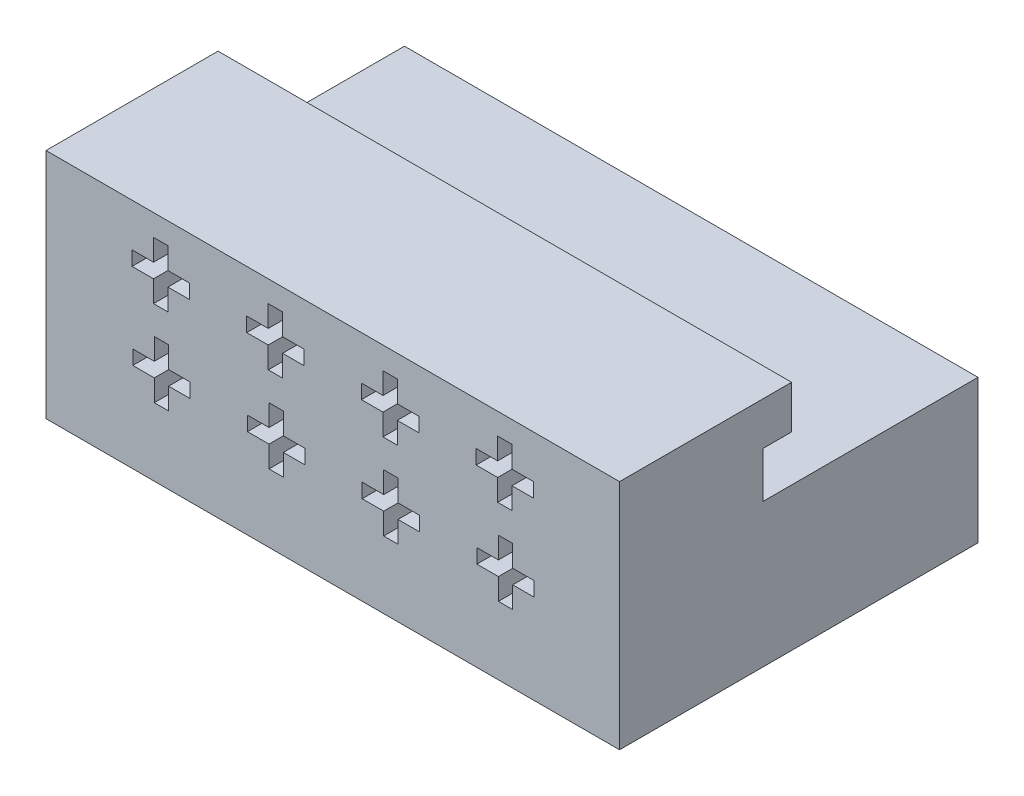
SolidWorks part; units mm, degrees
ref_plane "Front Plane" through (0, 0, 0) normal (0, 0, 1) x (1, 0, 0)
ref_plane "Top Plane" through (0, 0, 0) normal (0, 1, 0) x (1, 0, 0)
ref_plane "Right Plane" through (0, 0, 0) normal (1, 0, 0) x (0, 0, -1)
sketch "Sketch1" plane through (0, 0, 0) normal (1, 0, 0) x (0, 0, -1)
  line L0 (-9.6386, 6.2) -> (2.3614, 6.2)
  line L1 (2.3614, 6.2) -> (2.3614, 3.2)
  line L2 (2.3614, 3.2) -> (0.3614, 3.2)
  line L3 (0.3614, 3.2) -> (0.3614, 0)
  line L4 (0.3614, 0) -> (15.3614, 0)
  line L5 (15.3614, 0) -> (15.3614, -10)
  line L6 (15.3614, -10) -> (-9.6386, -10)
  line L7 (-9.6386, -10) -> (-9.6386, 6.2)
  dimension "D1" = 3.2
  dimension "D2" = 2
  dimension "D3" = 3
  dimension "D4" = 10
  dimension "D5" = 15
  dimension "D6" = 10
extrude "Boss-Extrude1" add sketch "Sketch1" along normal blind 40
sketch "Sketch2" plane through (0, 0, 9.6386) normal (0, 0, 1) x (1, 0, 0)
  line L0 (6, 3.2) -> (7.5, 3.2)
  line L1 (7.5, 3.2) -> (7.5, 4.7)
  line L2 (7.5, 4.7) -> (8.5, 4.7)
  line L3 (8.5, 4.7) -> (8.5, 3.2)
  line L4 (8.5, 3.2) -> (10, 3.2)
  line L5 (10, 3.2) -> (10, 2.2)
  line L6 (10, 2.2) -> (8.5, 2.2)
  line L7 (8.5, 2.2) -> (8.5, 0.7)
  line L8 (8.5, 0.7) -> (7.5, 0.7)
  line L9 (7.5, 0.7) -> (7.5, 2.2)
  line L10 (7.5, 2.2) -> (6, 2.2)
  line L11 (6, 2.2) -> (6, 3.2)
  line L12 (14, 3.2) -> (15.5, 3.2)
  line L13 (15.5, 3.2) -> (15.5, 4.7)
  line L14 (15.5, 4.7) -> (16.5, 4.7)
  line L15 (16.5, 4.7) -> (16.5, 3.2)
  line L16 (16.5, 3.2) -> (18, 3.2)
  line L17 (18, 3.2) -> (18, 2.2)
  line L18 (18, 2.2) -> (16.5, 2.2)
  line L19 (16.5, 2.2) -> (16.5, 0.7)
  line L20 (16.5, 0.7) -> (15.5, 0.7)
  line L21 (15.5, 0.7) -> (15.5, 2.2)
  line L22 (15.5, 2.2) -> (14, 2.2)
  line L23 (14, 2.2) -> (14, 3.2)
  line L24 (30, 3.2) -> (31.5, 3.2)
  line L25 (31.5, 3.2) -> (31.5, 4.7)
  line L26 (31.5, 4.7) -> (32.5, 4.7)
  line L27 (32.5, 4.7) -> (32.5, 3.2)
  line L28 (32.5, 3.2) -> (34, 3.2)
  line L29 (34, 3.2) -> (34, 2.2)
  line L30 (34, 2.2) -> (32.5, 2.2)
  line L31 (32.5, 2.2) -> (32.5, 0.7)
  line L32 (32.5, 0.7) -> (31.5, 0.7)
  line L33 (31.5, 0.7) -> (31.5, 2.2)
  line L34 (31.5, 2.2) -> (30, 2.2)
  line L35 (30, 2.2) -> (30, 3.2)
  line L60 (40, 6.2) -> (0, 6.2) construction
  line L61 (0, 6.2) -> (0, -10) construction
  line L62 (22, 3.1496) -> (23.5, 3.1496)
  line L63 (23.5, 3.1496) -> (23.5, 4.6496)
  line L64 (23.5, 4.6496) -> (24.5, 4.6496)
  line L65 (24.5, 4.6496) -> (24.5, 3.1496)
  line L66 (24.5, 3.1496) -> (26, 3.1496)
  line L67 (26, 3.1496) -> (26, 2.1496)
  line L68 (26, 2.1496) -> (24.5, 2.1496)
  line L69 (24.5, 2.1496) -> (24.5, 0.6496)
  line L70 (24.5, 0.6496) -> (23.5, 0.6496)
  line L71 (23.5, 0.6496) -> (23.5, 2.1496)
  line L72 (23.5, 2.1496) -> (22, 2.1496)
  line L73 (22, 2.1496) -> (22, 3.1496)
  line L74 (40, 6.2) -> (40, -10) construction
  line L75 (6.0514, -2.7582) -> (7.5514, -2.7582)
  line L76 (7.5514, -2.7582) -> (7.5514, -1.2582)
  line L77 (7.5514, -1.2582) -> (8.5514, -1.2582)
  line L78 (8.5514, -1.2582) -> (8.5514, -2.7582)
  line L79 (8.5514, -2.7582) -> (10.0514, -2.7582)
  line L80 (10.0514, -2.7582) -> (10.0514, -3.7582)
  line L81 (10.0514, -3.7582) -> (8.5514, -3.7582)
  line L82 (8.5514, -3.7582) -> (8.5514, -5.2582)
  line L83 (8.5514, -5.2582) -> (7.5514, -5.2582)
  line L84 (7.5514, -5.2582) -> (7.5514, -3.7582)
  line L85 (7.5514, -3.7582) -> (6.0514, -3.7582)
  line L86 (6.0514, -3.7582) -> (6.0514, -2.7582)
  line L87 (14.0514, -2.7582) -> (15.5514, -2.7582)
  line L88 (15.5514, -2.7582) -> (15.5514, -1.2582)
  line L89 (15.5514, -1.2582) -> (16.5514, -1.2582)
  line L90 (16.5514, -1.2582) -> (16.5514, -2.7582)
  line L91 (16.5514, -2.7582) -> (18.0514, -2.7582)
  line L92 (18.0514, -2.7582) -> (18.0514, -3.7582)
  line L93 (18.0514, -3.7582) -> (16.5514, -3.7582)
  line L94 (16.5514, -3.7582) -> (16.5514, -5.2582)
  line L95 (16.5514, -5.2582) -> (15.5514, -5.2582)
  line L96 (15.5514, -5.2582) -> (15.5514, -3.7582)
  line L97 (15.5514, -3.7582) -> (14.0514, -3.7582)
  line L98 (14.0514, -3.7582) -> (14.0514, -2.7582)
  line L99 (30.0514, -2.7582) -> (31.5514, -2.7582)
  line L100 (31.5514, -2.7582) -> (31.5514, -1.2582)
  line L101 (31.5514, -1.2582) -> (32.5514, -1.2582)
  line L102 (32.5514, -1.2582) -> (32.5514, -2.7582)
  line L103 (32.5514, -2.7582) -> (34.0514, -2.7582)
  line L104 (34.0514, -2.7582) -> (34.0514, -3.7582)
  line L105 (34.0514, -3.7582) -> (32.5514, -3.7582)
  line L106 (32.5514, -3.7582) -> (32.5514, -5.2582)
  line L107 (32.5514, -5.2582) -> (31.5514, -5.2582)
  line L108 (31.5514, -5.2582) -> (31.5514, -3.7582)
  line L109 (31.5514, -3.7582) -> (30.0514, -3.7582)
  line L110 (30.0514, -3.7582) -> (30.0514, -2.7582)
  line L111 (22.0514, -2.8086) -> (23.5514, -2.8086)
  line L112 (23.5514, -2.8086) -> (23.5514, -1.3086)
  line L113 (23.5514, -1.3086) -> (24.5514, -1.3086)
  line L114 (24.5514, -1.3086) -> (24.5514, -2.8086)
  line L115 (24.5514, -2.8086) -> (26.0514, -2.8086)
  line L116 (26.0514, -2.8086) -> (26.0514, -3.8086)
  line L117 (26.0514, -3.8086) -> (24.5514, -3.8086)
  line L118 (24.5514, -3.8086) -> (24.5514, -5.3086)
  line L119 (24.5514, -5.3086) -> (23.5514, -5.3086)
  line L120 (23.5514, -5.3086) -> (23.5514, -3.8086)
  line L121 (23.5514, -3.8086) -> (22.0514, -3.8086)
  line L122 (22.0514, -3.8086) -> (22.0514, -2.8086)
  point P48 (0, 0)
  point P49 (0, 0)
  point P52 (22, 2.6496)
  point P62 (16, 4.7)
  point P63 (6, 2.7)
  point P66 (14, 2.7)
  point P108 (22.0514, -3.3086)
  point P109 (16.0514, -1.2582)
  point P110 (6.0514, -3.2582)
  point P111 (14.0514, -3.2582)
  dimension "D1" = 1
  dimension "D2" = 1
  dimension "D3" = 1
  dimension "D4" = 1
  dimension "D5" = 4
  dimension "D6" = 4
  dimension "D7" = 1.5
  dimension "D8" = 1.5
  dimension "D9" = 1.5
  dimension "D10" = 1.5
  dimension "D11" = 1.5
  dimension "D12" = 1.5
  dimension "D13" = 1.5
  dimension "D14" = 6
  dimension "D15" = 4
  dimension "D16" = 6
  dimension "D17" = 4
  dimension "D18" = 1
  dimension "D19" = 1.5
  dimension "D20" = 1.5
  dimension "D21" = 1.5
  dimension "D22" = 1.5
  dimension "D23" = 1
  dimension "D24" = 1
  dimension "D25" = 1
  dimension "D26" = 1.5
  dimension "D27" = 1.5
  dimension "D28" = 1.5
  dimension "D29" = 1.5
  dimension "D30" = 1
  dimension "D31" = 1
  dimension "D32" = 1
  dimension "D33" = 1
  dimension "D34" = 1.5
  dimension "D35" = 1.5
  dimension "D36" = 1.5
  dimension "D37" = 4
extrude "Cut-Extrude3" cut sketch "Sketch2" against normal blind 8 contours L23 L22 L21 L20 L19 L18 L17 L16 L15 L14 L13 L12 | L98 L97 L96 L95 L94 L93 L92 L91 L90 L89 L88 L87 | L122 L121 L120 L119 L118 L117 L116 L115 L114 L113 L112 L111 | L73 L72 L71 L70 L69 L68 L67 L66 L65 L64 L63 L62 | L35 L34 L33 L32 L31 L30 L29 L28 L27 L26 L25 L24 | L110 L109 L108 L107 L106 L105 L104 L103 L102 L101 L100 L99 | L11 L0 L1 L2 L3 L4 L5 L6 L7 L8 L9 L10 | L75 L76 L77 L78 L79 L80 L81 L82 L83 L84 L85 L86
